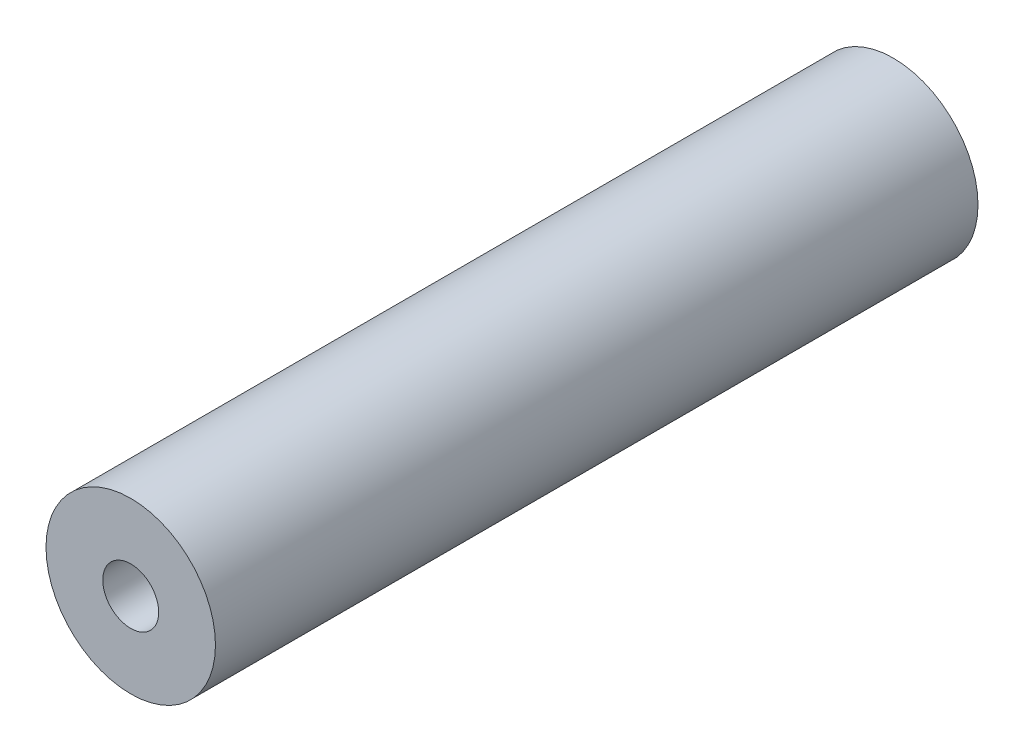
SolidWorks part; units mm, degrees
ref_plane "正面" through (0, 0, 0) normal (0, 0, 1) x (1, 0, 0)
ref_plane "平面" through (0, 0, 0) normal (0, 1, 0) x (1, 0, 0)
ref_plane "右側面" through (0, 0, 0) normal (1, 0, 0) x (0, 0, -1)
sketch "ｽｹｯﾁ1" plane through (0, 0, 0) normal (0, 0, 1) x (1, 0, 0)
  circle A0 centre (0, 0) radius 5
  dimension "D1" = 10
extrude "ﾎﾞｽ - 押し出し1" add sketch "ｽｹｯﾁ1" along normal blind 45
hole_wizard "M4x0.7 ねじ穴1" positions "ｽｹｯﾁ2" profile "ｽｹｯﾁ3" tap size "M4x0.7" standard "JIS"
sketch "ｽｹｯﾁ2" plane through (0, 0, 45) normal (0, 0, 1) x (1, 0, 0)
  point P0 (0, 0)
sketch "ｽｹｯﾁ3" plane through (0, 0, 45) normal (1, 0, 0) x (0, -1, 0)
  line L0 (0, 0) -> (0, 15.9914)
  line L1 (0, 15.9914) -> (1.65, 15)
  line L2 (1.65, 15) -> (1.65, 0)
  line L5 (1.65, 0) -> (0, 0)
  line L10 (0, 15.9914) -> (-1.65, 15) construction
  line L11 (0, -6.35) -> (0, 107.95) construction
  dimension "ねじ下穴ﾄﾞﾘﾙ直径" = 3.3
  dimension "ねじ下穴ﾄﾞﾘﾙの深さ" = 15
  dimension "ﾄﾞﾘﾙ角度" = 118
ref_plane "平面1" through (0, 0, 22.5) normal (0, 0, 1) x (1, 0, 0)
mirror "ﾐﾗｰ1" about plane through (0, 0, 22.5) normal (0, 0, 1) of "M4x0.7 ねじ穴1"
